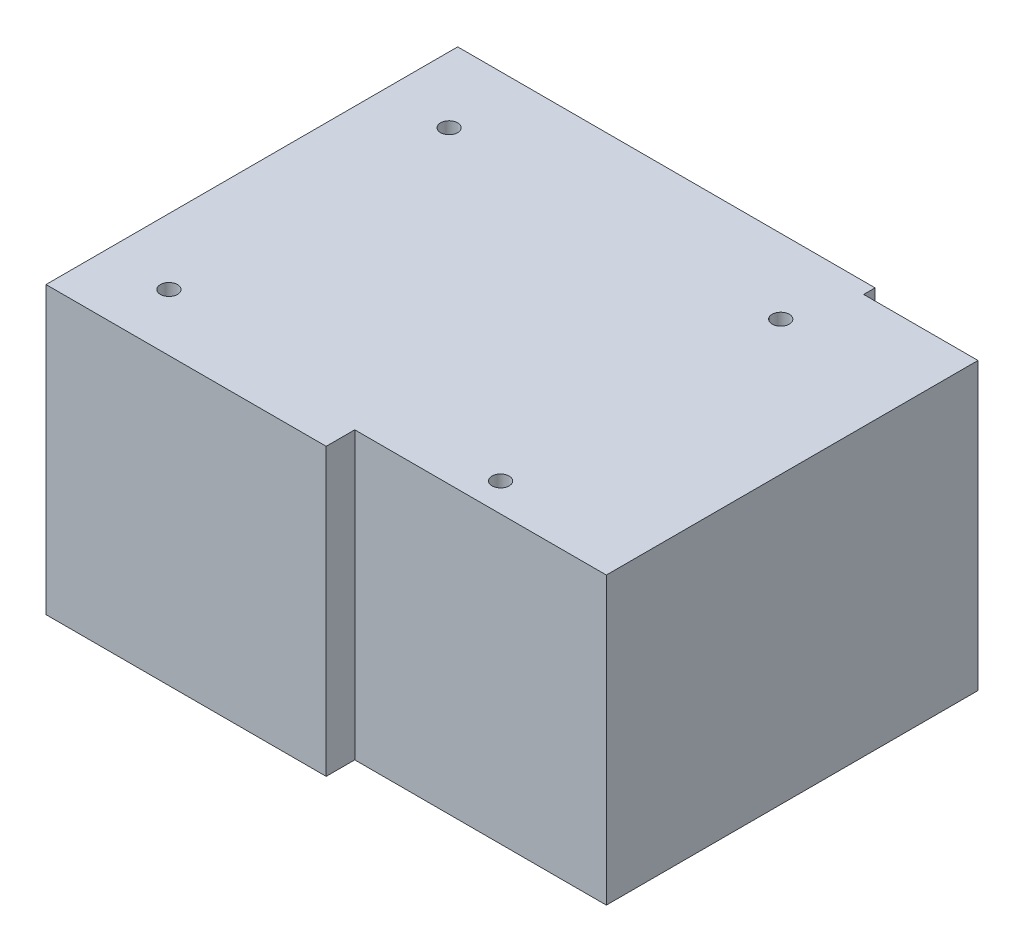
SolidWorks part; units mm, degrees
ref_plane "前基準面" through (0, 0, 0) normal (0, 0, 1) x (1, 0, 0)
ref_plane "上基準面" through (0, 0, 0) normal (0, 1, 0) x (1, 0, 0)
ref_plane "右基準面" through (0, 0, 0) normal (1, 0, 0) x (0, 0, -1)
sketch "草圖1" plane through (0, 0, 0) normal (0, 1, 0) x (1, 0, 0)
  line L1 (0, 0) -> (49, 0)
  line L2 (0, 0) -> (0, 72)
  line L3 (0, 72) -> (52.1817, 72)
  line L4 (49, 0) -> (49, 5)
  line L5 (52.1817, 72) -> (73, 72)
  line L8 (73, 72) -> (73, 70)
  line L11 (49, 5) -> (93, 5)
  line L12 (93, 70) -> (93, 5)
  line L13 (73, 70) -> (93, 70)
  point P5 (73, 71)
  dimension "D1" = 93
  dimension "D2" = 72
  dimension "D3" = 2
  dimension "D4" = 5
  dimension "D5" = 49
  dimension "D6" = 73
extrude "填料-伸長1" add sketch "草圖1" along normal blind 50
sketch "草圖2" plane through (0, 50, 0) normal (0, 1, 0) x (1, 0, 0)
  line L0 (73, 72) -> (0, 72) construction
  line L1 (0, 72) -> (0, 0) construction
  line L3 (11.5, 59) -> (69.5, 59) construction
  line L4 (11.5, 59) -> (11.5, 10) construction
  line L5 (11.5, 10) -> (69.5, 10) construction
  line L6 (69.5, 59) -> (69.5, 10) construction
  circle A0 centre (11.5, 59) radius 1.5
  circle A1 centre (69.5, 59) radius 1.5
  circle A2 centre (69.5, 10) radius 1.5
  circle A3 centre (11.5, 10) radius 1.5
  dimension "D2" = 11.5
  dimension "D3" = 3
  dimension "D1" = 13
  dimension "D4" = 58
  dimension "D5" = 49
extrude "除料-伸長1" cut sketch "草圖2" against normal through all
